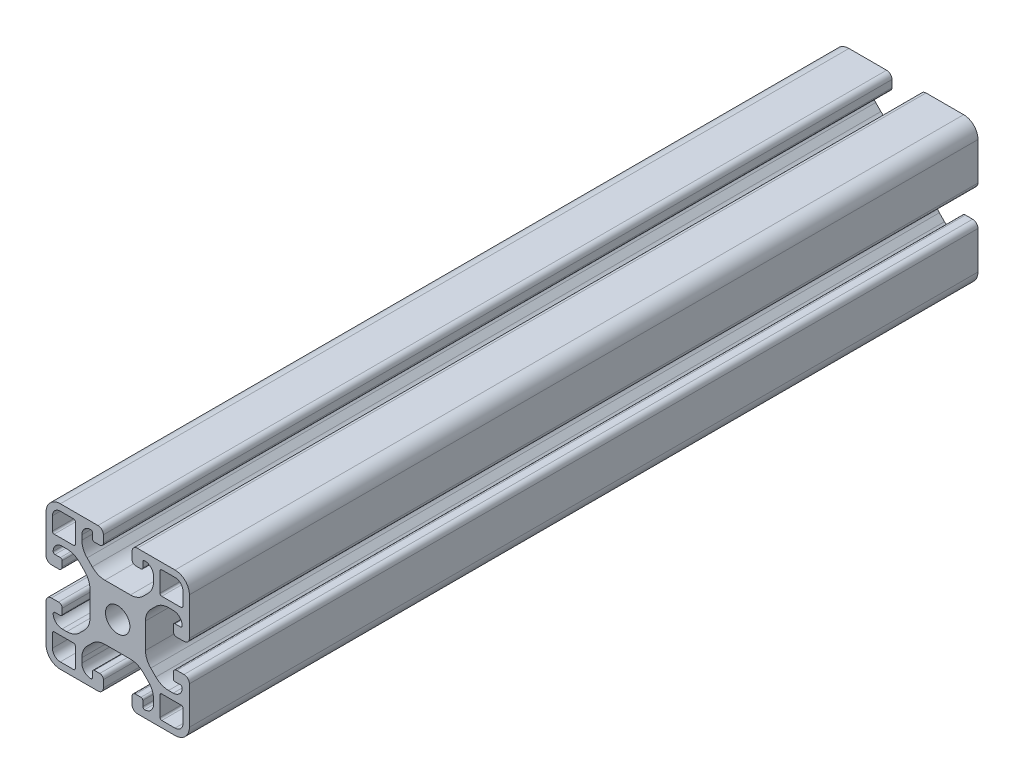
SolidWorks part; units mm, degrees
ref_plane "Plan de face" through (0, 0, 0) normal (0, 0, 1) x (1, 0, 0)
ref_plane "Plan de dessus" through (0, 0, 0) normal (0, 1, 0) x (1, 0, 0)
ref_plane "Plan de droite" through (0, 0, 0) normal (1, 0, 0) x (0, 0, -1)
ref_plane "Plan1" through (0, 0, -30) normal (0, 0, -1) x (-1, 0, 0)
sketch "Esquisse1" plane through (0, 0, -30) normal (0, 0, -1) x (-1, 0, 0)
  line L0 (-4.5, 15) -> (-4.5, 13.5)
  line L1 (-4, 13) -> (-2.5, 13)
  line L2 (-4.5, 10) -> (-5.8076, 10)
  line L3 (-9.3431, 11.4645) -> (-10.7855, 12.9069)
  line L4 (-12.25, 16.4424) -> (-12.25, 23.5576)
  line L5 (-10.7855, 27.0931) -> (-9.3431, 28.5355)
  line L6 (-5.8076, 30) -> (-4.5, 30)
  line L7 (-2.5, 27) -> (-4, 27)
  line L8 (-4.5, 26.5) -> (-4.5, 25)
  line L9 (-3.5, 24) -> (-1.5, 24)
  line L10 (0, 25.5) -> (0, 36)
  line L11 (-4, 40) -> (-14.5, 40)
  line L12 (-16, 38.5) -> (-16, 36.5)
  line L13 (-15, 35.5) -> (-13.5, 35.5)
  line L14 (-13, 36) -> (-13, 37.5)
  line L15 (-10, 35.5) -> (-10, 34.1924)
  line L16 (-11.4645, 30.6569) -> (-12.9069, 29.2145)
  line L17 (-16.4424, 27.75) -> (-23.5576, 27.75)
  line L18 (-27.0931, 29.2145) -> (-28.5355, 30.6569)
  line L19 (-30, 34.1924) -> (-30, 35.5)
  line L20 (-27, 37.5) -> (-27, 36)
  line L21 (-26.5, 35.5) -> (-25, 35.5)
  line L22 (-24, 36.5) -> (-24, 38.5)
  line L23 (-25.5, 40) -> (-36, 40)
  line L24 (-40, 36) -> (-40, 25.5)
  line L25 (-38.5, 24) -> (-36.5, 24)
  line L26 (-35.5, 25) -> (-35.5, 26.5)
  line L27 (-36, 27) -> (-37.5, 27)
  line L28 (-35.5, 30) -> (-34.1924, 30)
  line L29 (-30.6569, 28.5355) -> (-29.2145, 27.0931)
  line L30 (-27.75, 23.5576) -> (-27.75, 16.4424)
  line L31 (-29.2145, 12.9069) -> (-30.6569, 11.4645)
  line L32 (-34.1924, 10) -> (-35.5, 10)
  line L33 (-37.5, 13) -> (-36, 13)
  line L34 (-35.5, 13.5) -> (-35.5, 15)
  line L35 (-36.5, 16) -> (-38.5, 16)
  line L36 (-40, 14.5) -> (-40, 4)
  line L37 (-36, 0) -> (-25.5, 0)
  line L38 (-24, 1.5) -> (-24, 3.5)
  line L39 (-25, 4.5) -> (-26.5, 4.5)
  line L40 (-27, 4) -> (-27, 2.5)
  line L41 (-30, 4.5) -> (-30, 5.8076)
  line L42 (-28.5355, 9.3431) -> (-27.0931, 10.7855)
  line L43 (-23.5576, 12.25) -> (-16.4424, 12.25)
  line L44 (-12.9069, 10.7855) -> (-11.4645, 9.3431)
  line L45 (-10, 5.8076) -> (-10, 4.5)
  line L46 (-13, 2.5) -> (-13, 4)
  line L47 (-13.5, 4.5) -> (-15, 4.5)
  line L48 (-16, 3.5) -> (-16, 1.5)
  line L49 (-14.5, 0) -> (-4, 0)
  line L50 (0, 4) -> (0, 14.5)
  line L51 (-1.5, 16) -> (-3.5, 16)
  line L52 (-4, 1.8) -> (-7.7, 1.8)
  line L53 (-8.2, 2.3) -> (-8.2, 7.7)
  line L54 (-7.7, 8.2) -> (-2.3, 8.2)
  line L55 (-1.8, 7.7) -> (-1.8, 4)
  line L56 (-38.2, 4) -> (-38.2, 7.7)
  line L57 (-37.7, 8.2) -> (-32.3, 8.2)
  line L58 (-31.8, 7.7) -> (-31.8, 2.3)
  line L59 (-32.3, 1.8) -> (-36, 1.8)
  line L60 (-36, 38.2) -> (-32.3, 38.2)
  line L61 (-31.8, 37.7) -> (-31.8, 32.3)
  line L62 (-32.3, 31.8) -> (-37.7, 31.8)
  line L63 (-38.2, 32.3) -> (-38.2, 36)
  line L64 (-1.8, 36) -> (-1.8, 32.3)
  line L65 (-2.3, 31.8) -> (-7.7, 31.8)
  line L66 (-8.2, 32.3) -> (-8.2, 37.7)
  line L67 (-7.7, 38.2) -> (-4, 38.2)
  arc A0 (-4.5, 13.5) -> (-4, 13) centre (-4, 13.5) ccw
  arc A1 (-2.5, 13) -> (-2, 12.5) centre (-2.5, 12.5) cw
  arc A2 (-2, 12.5) -> (-4.5, 10) centre (-4.5, 12.5) cw
  arc A3 (-5.8076, 10) -> (-9.3431, 11.4645) centre (-5.8076, 15) cw
  arc A4 (-10.7855, 12.9069) -> (-12.25, 16.4424) centre (-7.25, 16.4424) cw
  arc A5 (-12.25, 23.5576) -> (-10.7855, 27.0931) centre (-7.25, 23.5576) cw
  arc A6 (-9.3431, 28.5355) -> (-5.8076, 30) centre (-5.8076, 25) cw
  arc A7 (-4.5, 30) -> (-2, 27.5) centre (-4.5, 27.5) cw
  arc A8 (-2, 27.5) -> (-2.5, 27) centre (-2.5, 27.5) cw
  arc A9 (-4, 27) -> (-4.5, 26.5) centre (-4, 26.5) ccw
  arc A10 (-4.5, 25) -> (-3.5, 24) centre (-3.5, 25) ccw
  arc A11 (-1.5, 24) -> (0, 25.5) centre (-1.5, 25.5) ccw
  arc A12 (0, 36) -> (-4, 40) centre (-4, 36) ccw
  arc A13 (-14.5, 40) -> (-16, 38.5) centre (-14.5, 38.5) ccw
  arc A14 (-16, 36.5) -> (-15, 35.5) centre (-15, 36.5) ccw
  arc A15 (-13.5, 35.5) -> (-13, 36) centre (-13.5, 36) ccw
  arc A16 (-13, 37.5) -> (-12.5, 38) centre (-12.5, 37.5) cw
  arc A17 (-12.5, 38) -> (-10, 35.5) centre (-12.5, 35.5) cw
  arc A18 (-10, 34.1924) -> (-11.4645, 30.6569) centre (-15, 34.1924) cw
  arc A19 (-12.9069, 29.2145) -> (-16.4424, 27.75) centre (-16.4424, 32.75) cw
  arc A20 (-23.5576, 27.75) -> (-27.0931, 29.2145) centre (-23.5576, 32.75) cw
  arc A21 (-28.5355, 30.6569) -> (-30, 34.1924) centre (-25, 34.1924) cw
  arc A22 (-30, 35.5) -> (-27.5, 38) centre (-27.5, 35.5) cw
  arc A23 (-27.5, 38) -> (-27, 37.5) centre (-27.5, 37.5) cw
  arc A24 (-27, 36) -> (-26.5, 35.5) centre (-26.5, 36) ccw
  arc A25 (-25, 35.5) -> (-24, 36.5) centre (-25, 36.5) ccw
  arc A26 (-24, 38.5) -> (-25.5, 40) centre (-25.5, 38.5) ccw
  arc A27 (-36, 40) -> (-40, 36) centre (-36, 36) ccw
  arc A28 (-40, 25.5) -> (-38.5, 24) centre (-38.5, 25.5) ccw
  arc A29 (-36.5, 24) -> (-35.5, 25) centre (-36.5, 25) ccw
  arc A30 (-35.5, 26.5) -> (-36, 27) centre (-36, 26.5) ccw
  arc A31 (-37.5, 27) -> (-38, 27.5) centre (-37.5, 27.5) cw
  arc A32 (-38, 27.5) -> (-35.5, 30) centre (-35.5, 27.5) cw
  arc A33 (-34.1924, 30) -> (-30.6569, 28.5355) centre (-34.1924, 25) cw
  arc A34 (-29.2145, 27.0931) -> (-27.75, 23.5576) centre (-32.75, 23.5576) cw
  arc A35 (-27.75, 16.4424) -> (-29.2145, 12.9069) centre (-32.75, 16.4424) cw
  arc A36 (-30.6569, 11.4645) -> (-34.1924, 10) centre (-34.1924, 15) cw
  arc A37 (-35.5, 10) -> (-38, 12.5) centre (-35.5, 12.5) cw
  arc A38 (-38, 12.5) -> (-37.5, 13) centre (-37.5, 12.5) cw
  arc A39 (-36, 13) -> (-35.5, 13.5) centre (-36, 13.5) ccw
  arc A40 (-35.5, 15) -> (-36.5, 16) centre (-36.5, 15) ccw
  arc A41 (-38.5, 16) -> (-40, 14.5) centre (-38.5, 14.5) ccw
  arc A42 (-40, 4) -> (-36, 0) centre (-36, 4) ccw
  arc A43 (-25.5, 0) -> (-24, 1.5) centre (-25.5, 1.5) ccw
  arc A44 (-24, 3.5) -> (-25, 4.5) centre (-25, 3.5) ccw
  arc A45 (-26.5, 4.5) -> (-27, 4) centre (-26.5, 4) ccw
  arc A46 (-27, 2.5) -> (-27.5, 2) centre (-27.5, 2.5) cw
  arc A47 (-27.5, 2) -> (-30, 4.5) centre (-27.5, 4.5) cw
  arc A48 (-30, 5.8076) -> (-28.5355, 9.3431) centre (-25, 5.8076) cw
  arc A49 (-27.0931, 10.7855) -> (-23.5576, 12.25) centre (-23.5576, 7.25) cw
  arc A50 (-16.4424, 12.25) -> (-12.9069, 10.7855) centre (-16.4424, 7.25) cw
  arc A51 (-11.4645, 9.3431) -> (-10, 5.8076) centre (-15, 5.8076) cw
  arc A52 (-10, 4.5) -> (-12.5, 2) centre (-12.5, 4.5) cw
  arc A53 (-12.5, 2) -> (-13, 2.5) centre (-12.5, 2.5) cw
  arc A54 (-13, 4) -> (-13.5, 4.5) centre (-13.5, 4) ccw
  arc A55 (-15, 4.5) -> (-16, 3.5) centre (-15, 3.5) ccw
  arc A56 (-16, 1.5) -> (-14.5, 0) centre (-14.5, 1.5) ccw
  arc A57 (-4, 0) -> (0, 4) centre (-4, 4) ccw
  arc A58 (0, 14.5) -> (-1.5, 16) centre (-1.5, 14.5) ccw
  arc A59 (-3.5, 16) -> (-4.5, 15) centre (-3.5, 15) ccw
  circle A60 centre (-20, 20) radius 3.4
  arc A61 (-1.8, 4) -> (-4, 1.8) centre (-4, 4) cw
  arc A62 (-7.7, 1.8) -> (-8.2, 2.3) centre (-7.7, 2.3) cw
  arc A63 (-8.2, 7.7) -> (-7.7, 8.2) centre (-7.7, 7.7) cw
  arc A64 (-2.3, 8.2) -> (-1.8, 7.7) centre (-2.3, 7.7) cw
  arc A65 (-36, 1.8) -> (-38.2, 4) centre (-36, 4) cw
  arc A66 (-38.2, 7.7) -> (-37.7, 8.2) centre (-37.7, 7.7) cw
  arc A67 (-32.3, 8.2) -> (-31.8, 7.7) centre (-32.3, 7.7) cw
  arc A68 (-31.8, 2.3) -> (-32.3, 1.8) centre (-32.3, 2.3) cw
  arc A69 (-38.2, 36) -> (-36, 38.2) centre (-36, 36) cw
  arc A70 (-32.3, 38.2) -> (-31.8, 37.7) centre (-32.3, 37.7) cw
  arc A71 (-31.8, 32.3) -> (-32.3, 31.8) centre (-32.3, 32.3) cw
  arc A72 (-37.7, 31.8) -> (-38.2, 32.3) centre (-37.7, 32.3) cw
  arc A73 (-4, 38.2) -> (-1.8, 36) centre (-4, 36) cw
  arc A74 (-1.8, 32.3) -> (-2.3, 31.8) centre (-2.3, 32.3) cw
  arc A75 (-7.7, 31.8) -> (-8.2, 32.3) centre (-7.7, 32.3) cw
  arc A76 (-8.2, 37.7) -> (-7.7, 38.2) centre (-7.7, 37.7) cw
extrude "Boss.-Extru.1" add sketch "Esquisse1" against normal blind 220
